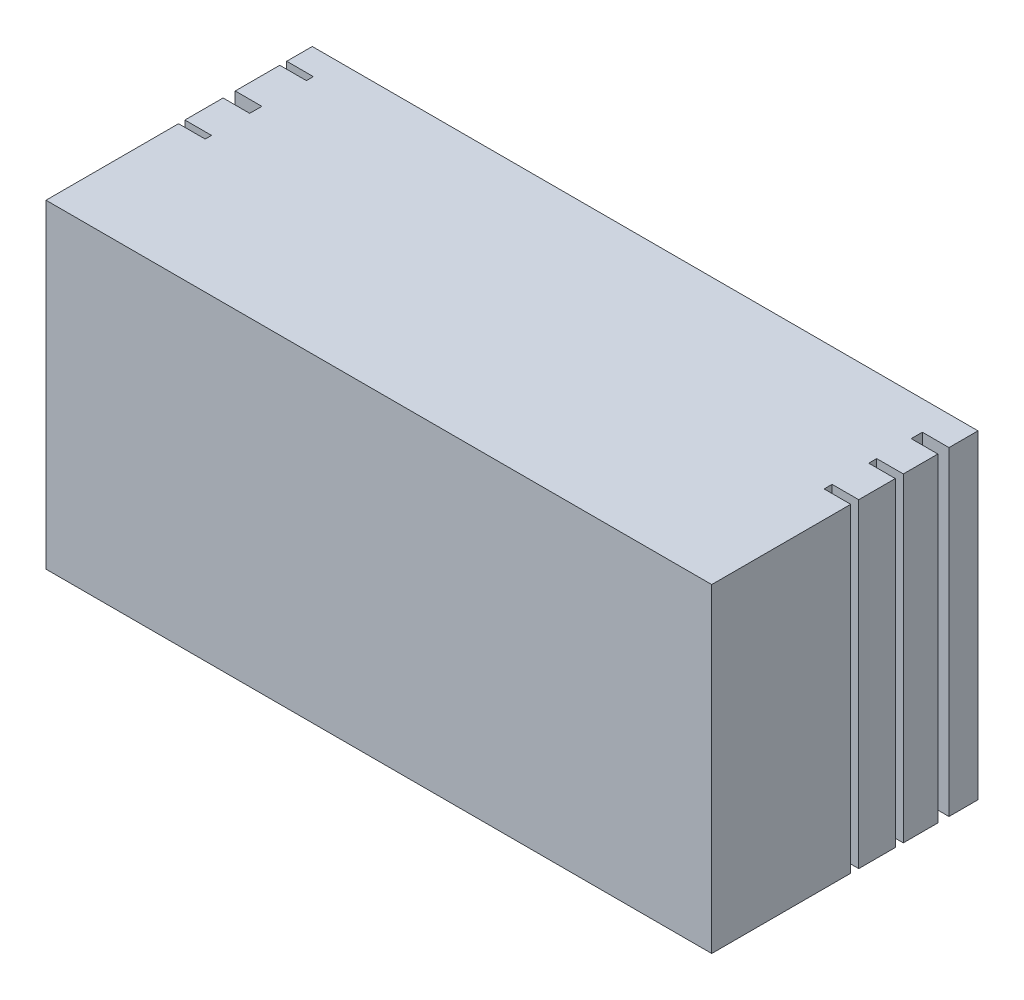
SolidWorks part; units mm, degrees
ref_plane "정면" through (0, 0, 0) normal (0, 0, 1) x (1, 0, 0)
ref_plane "윗면" through (0, 0, 0) normal (0, 1, 0) x (1, 0, 0)
ref_plane "우측면" through (0, 0, 0) normal (1, 0, 0) x (0, 0, -1)
sketch "스케치1" plane through (0, 0, 0) normal (0, 0, 1) x (1, 0, 0)
  line L1 (-80, 60) -> (170, 60)
  line L2 (-80, 60) -> (-80, -60)
  line L3 (-80, -60) -> (170, -60)
  line L4 (170, 60) -> (170, -60)
  dimension "D1" = 250
  dimension "D2" = 120
  dimension "D3" = 60
  dimension "D4" = 80
extrude "보스-돌출1" add sketch "스케치1" along normal blind 100
sketch "스케치2" plane through (170, 0, 0) normal (1, 0, 0) x (0, 0, -1)
  line L1 (-47.7966, 73.28) -> (-44.7966, 73.28)
  line L2 (-47.7966, 73.28) -> (-47.7966, -67.784)
  line L3 (-47.7966, -67.784) -> (-44.7966, -67.784)
  line L4 (-44.7966, 73.28) -> (-44.7966, -67.784)
  line L5 (-31.0469, 73.28) -> (-28.0469, 73.28)
  line L6 (-31.0469, 73.28) -> (-31.0469, -67.784)
  line L7 (-31.0469, -67.784) -> (-28.0469, -67.784)
  line L8 (-28.0469, 73.28) -> (-28.0469, -67.784)
  line L9 (-15.0823, 73.28) -> (-10.8949, 73.28)
  line L10 (-15.0823, 73.28) -> (-15.0823, -67.784)
  line L11 (-15.0823, -67.784) -> (-10.8949, -67.784)
  line L12 (-10.8949, 73.28) -> (-10.8949, -67.784)
  dimension "D1" = 3
  dimension "D2" = 3
extrude "컷-돌출1" cut sketch "스케치2" against normal blind 10
sketch "스케치3" plane through (-80, 0, 0) normal (-1, 0, 0) x (0, 0, 1)
  line L1 (9.6071, 69.9495) -> (12.2138, 69.9495)
  line L2 (9.6071, 69.9495) -> (9.6071, -68.8558)
  line L3 (9.6071, -68.8558) -> (12.2138, -68.8558)
  line L4 (12.2138, 69.9495) -> (12.2138, -68.8558)
  line L5 (28.9399, 69.9495) -> (33.5016, 69.9495)
  line L6 (28.9399, 69.9495) -> (28.9399, -68.8558)
  line L7 (28.9399, -68.8558) -> (33.5016, -68.8558)
  line L8 (33.5016, 69.9495) -> (33.5016, -68.8558)
  line L9 (47.8383, 69.9495) -> (50.2278, 69.9495)
  line L10 (47.8383, 69.9495) -> (47.8383, -68.8558)
  line L11 (47.8383, -68.8558) -> (50.2278, -68.8558)
  line L12 (50.2278, 69.9495) -> (50.2278, -68.8558)
extrude "컷-돌출2" cut sketch "스케치3" against normal blind 10
